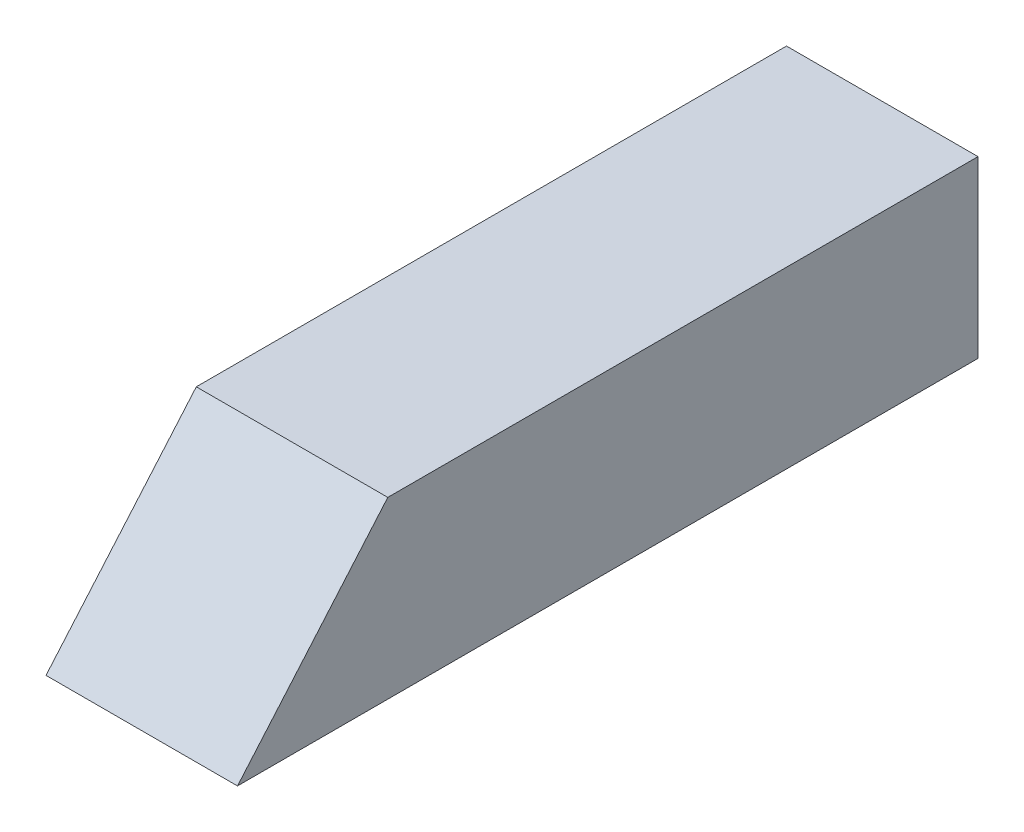
SolidWorks part; units mm, degrees
ref_plane "Front Plane" through (0, 0, 0) normal (0, 0, 1) x (1, 0, 0)
ref_plane "Top Plane" through (0, 0, 0) normal (0, 1, 0) x (1, 0, 0)
ref_plane "Right Plane" through (0, 0, 0) normal (1, 0, 0) x (0, 0, -1)
sketch "Sketch1" plane through (0, 0, 0) normal (0, 0, 1) x (1, 0, 0)
  line L1 (0, 0) -> (43.9658, 0)
  line L2 (0, 0) -> (0, -40.1241)
  line L3 (0, -40.1241) -> (43.9658, -40.1241)
  line L4 (43.9658, 0) -> (43.9658, -40.1241)
extrude "Boss-Extrude1" add sketch "Sketch1" along normal blind 170
sketch "Sketch2" plane through (43.9658, 0, 0) normal (1, 0, 0) x (0, 0, -1)
  line L0 (-170, -40.1241) -> (-135.4984, 0)
  line L1 (-170, 0) -> (0, 0) construction
  line L2 (-170, -40.1241) -> (-170, 0) construction
  line L3 (-170, -40.1241) -> (-170, 0)
  line L4 (-170, 0) -> (-135.4984, 0)
extrude "Cut-Extrude1" cut sketch "Sketch2" against normal through all
